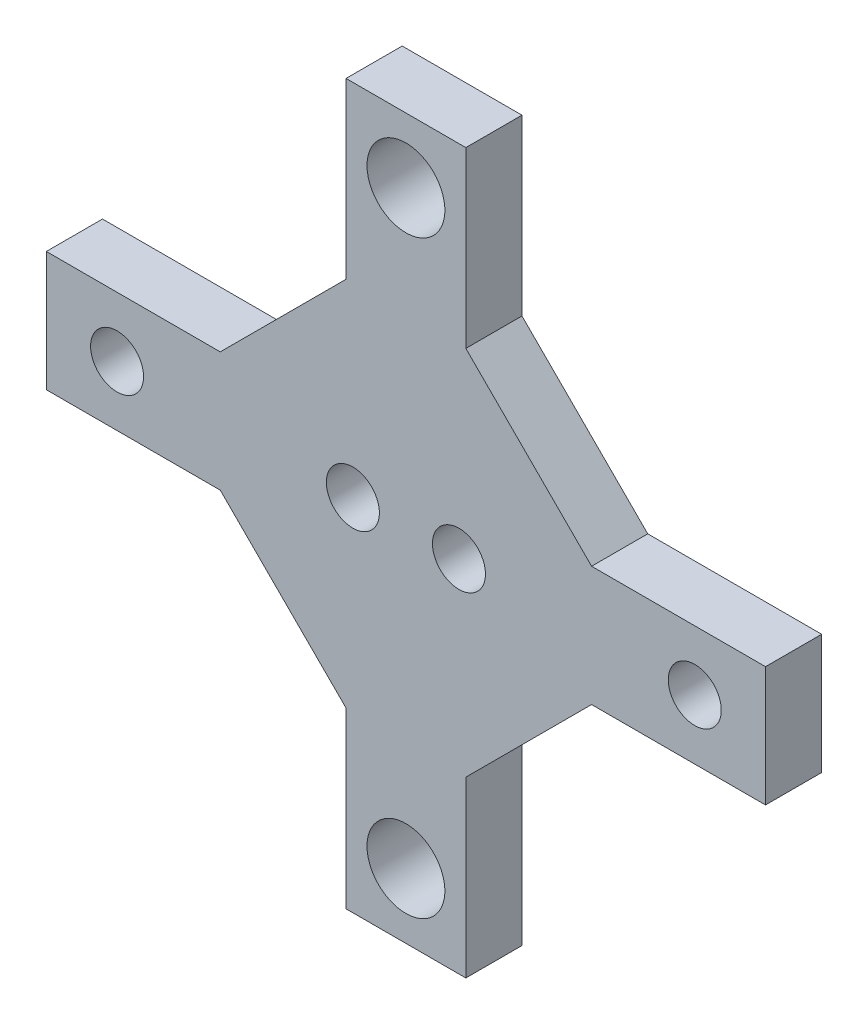
SolidWorks part; units mm, degrees
ref_plane "Front Plane" through (0, 0, 0) normal (0, 0, 1) x (1, 0, 0)
ref_plane "Top Plane" through (0, 0, 0) normal (0, 1, 0) x (1, 0, 0)
ref_plane "Right Plane" through (0, 0, 0) normal (1, 0, 0) x (0, 0, -1)
sketch "Sketch1" plane through (0, 0, 0) normal (0, 0, 1) x (1, 0, 0)
  line L0 (0, 30.5) -> (0, -30.5)
  line L1 (-5.08, 30.5) -> (5.08, 30.5)
  line L2 (-5.08, 30.5) -> (-5.08, -30.5)
  line L3 (-5.08, -30.5) -> (5.08, -30.5)
  line L4 (5.08, 30.5) -> (5.08, -30.5)
  line L5 (-30.5, 0) -> (30.5, 0)
  line L6 (-30.5, 5.08) -> (30.5, 5.08)
  line L7 (-30.5, 5.08) -> (-30.5, -5.08)
  line L8 (-30.5, -5.08) -> (30.5, -5.08)
  line L9 (30.5, 5.08) -> (30.5, -5.08)
  circle A0 centre (0, 25) radius 3.302
  circle A1 centre (0, -25) radius 3.302
  circle A2 centre (-24.5, 0) radius 2.2479
  circle A3 centre (24.5, 0) radius 2.2479
  circle A4 centre (-4.5, 0) radius 2.2479
  circle A5 centre (4.5, 0) radius 2.2479
  dimension "D5" = 50
  dimension "D11" = 49
  dimension "D13" = 20
  dimension "D14" = 20
  dimension "D1" = 61
  dimension "D2" = 30.5
  dimension "D3" = 10.16
  dimension "D4" = 5.08
  dimension "D6" = 25
  dimension "D7" = 61
  dimension "D8" = 30.5
  dimension "D9" = 10.16
  dimension "D10" = 5.08
  dimension "D12" = 24.5
extrude "Boss-Extrude5" add sketch "Sketch1" along normal blind 4.7625 contours A0 L0 L1 L2 L6 | A0 L0 L6 L4 L1 | A5 L5 A3 L9 L6 L4 | A5 L4 L8 L9 L5 A3 | A5 L5 L0 L8 L4 | A4 L2 L8 L0 L5 | A5 L4 L6 L0 L5 | A4 L5 L0 L6 L2 | A4 L2 L6 L7 L5 A2 | A4 L5 A2 L7 L8 L2 | A1 L0 L8 L2 L3 | A1 L0 L3 L4 L8
sketch "Sketch3" plane through (0, 0, 4.7625) normal (0, 0, 1) x (1, 0, 0)
  line L0 (-5.08, 5.08) -> (-5.08, 15.748)
  line L1 (-5.08, 30.5) -> (-5.08, 5.08) construction
  line L2 (-5.08, 5.08) -> (-15.748, 5.08)
  line L3 (-30.5, 5.08) -> (-5.08, 5.08) construction
  line L4 (-5.08, 15.748) -> (-15.748, 5.08)
  line L5 (15.748, 5.08) -> (5.08, 15.748)
  line L6 (5.08, -15.748) -> (15.748, -5.08)
  line L7 (-15.748, -5.08) -> (-5.08, -15.748)
  line M5 (5.08, -30.5) -> (5.08, -5.08)
  line M6 (5.08, -5.08) -> (30.5, -5.08)
  line M8 (30.5, 5.08) -> (5.08, 5.08)
  line M9 (5.08, 5.08) -> (5.08, 30.5)
  line M11 (-5.08, 30.5) -> (-5.08, 5.08)
  line M12 (-5.08, 5.08) -> (-30.5, 5.08)
  line M14 (-30.5, -5.08) -> (-5.08, -5.08)
  line M15 (-5.08, -5.08) -> (-5.08, -30.5)
  dimension "D1" = 10.668
  dimension "D2" = 10.668
  dimension "D3" = 4
extrude "Boss-Extrude6" add sketch "Sketch3" against normal blind 4.7625 contours L5 M8 M9 | L6 M5 M6 | L7 M14 M15 | L4 M11 M12
